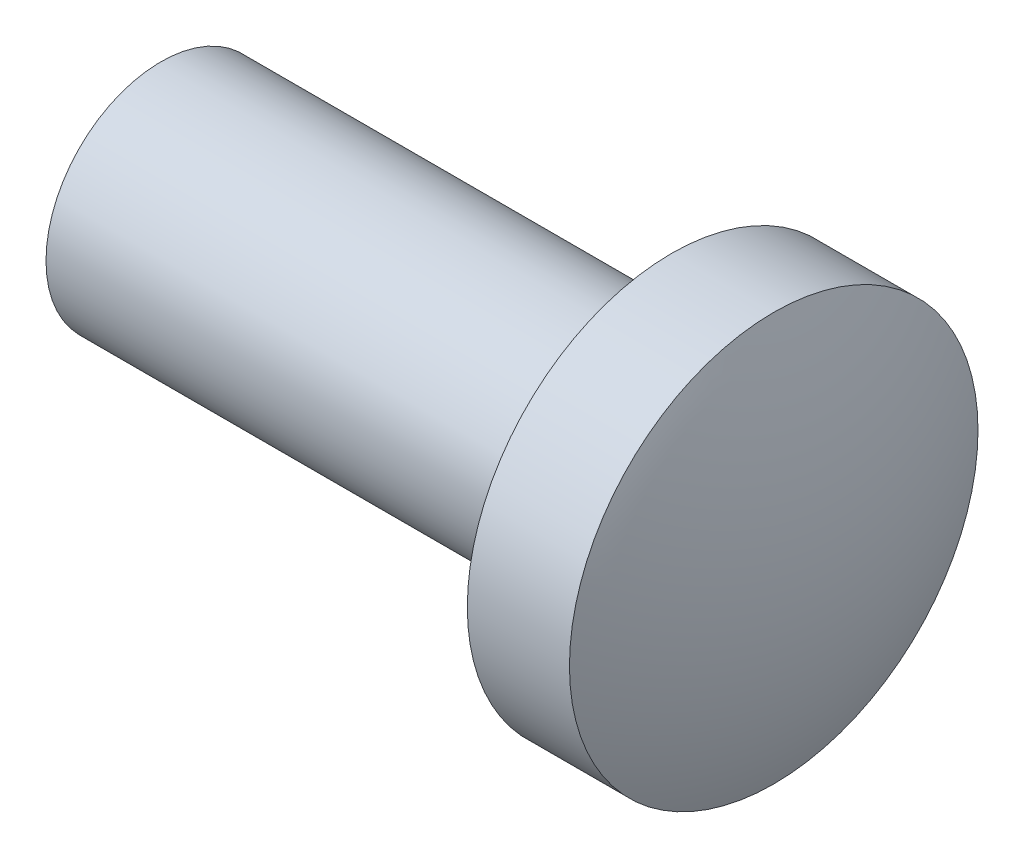
SolidWorks part; units mm, degrees
material "Zinc AC41A Alloy, As Cast"
ref_plane "Plan de face" through (0, 0, 0) normal (0, 0, 1) x (1, 0, 0)
ref_plane "Plan de dessus" through (0, 0, 0) normal (0, 1, 0) x (1, 0, 0)
ref_plane "Plan de droite" through (0, 0, 0) normal (1, 0, 0) x (0, 0, -1)
sketch "Sketch1" plane through (0, 0, 0) normal (0, 0, 1) x (1, 0, 0)
  line L0 (0, 0) -> (0, 2.25)
  line L1 (0, 2.25) -> (10, 2.25)
  line L2 (10, 2.25) -> (10, 4)
  line L3 (10, 4) -> (12, 4)
  line L4 (0, 0) -> (12.85, 0)
  arc A0 (12.85, 0) -> (12, 4) centre (3.0132, 0) ccw
  point P6 (0, 0)
  dimension "D6" = 9.8368
  dimension "D1" = 2.25
  dimension "D2" = 10
  dimension "D3" = 1.75
  dimension "D4" = 2
  dimension "D5" = 12.85
revolve "Revolve1" add sketch "Sketch1" angle 360 about L4
sketch "Sketch2" plane through (0, 0, 0) normal (-1, 0, 0) x (0, 0, 1)
  circle A0 centre (0, 0) radius 1.25
  dimension "D1" = 2.5
extrude "Cut-Extrude1" cut sketch "Sketch2" against normal blind 11.25
cosmetic thread "Cosmetic Thread2" parameters "D2"=3
sketch "Sketch3" plane through (11.25, 0, 0) normal (-1, 0, 0) x (0, 0, 1)
  circle A0 centre (0, 0) radius 1.7
  dimension "D1" = 3.4
extrude "Cut-Extrude2" cut sketch "Sketch3" against normal blind 0.35
